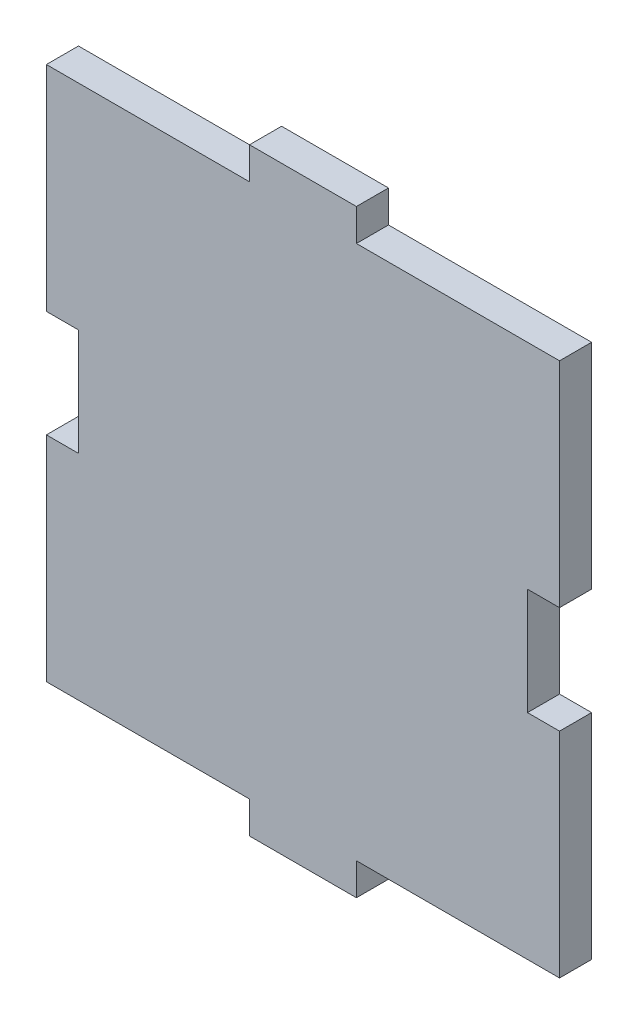
SolidWorks part; units mm, degrees
ref_plane "Front Plane" through (0, 0, 0) normal (0, 0, 1) x (1, 0, 0)
ref_plane "Top Plane" through (0, 0, 0) normal (0, 1, 0) x (1, 0, 0)
ref_plane "Right Plane" through (0, 0, 0) normal (1, 0, 0) x (0, 0, -1)
sketch "Sketch1" plane through (0, 0, 0) normal (0, 0, 1) x (1, 0, 0)
  line L0 (-5, -25) -> (-5, -28)
  line L1 (24, -25) -> (5, -25)
  line L2 (24, -25) -> (24, -5)
  line L3 (24, 25) -> (5, 25)
  line L4 (-24, -25) -> (-24, -5)
  line L5 (24, -25) -> (-24, 25) construction
  line L6 (24, 25) -> (-24, -25) construction
  line L7 (-5, -28) -> (5, -28)
  line L8 (5, -28) -> (5, -25)
  line L9 (-5, 25) -> (-5, 28)
  line L10 (-5, 28) -> (5, 28)
  line L11 (5, 28) -> (5, 25)
  line L12 (-24, -5) -> (-21, -5)
  line L13 (-21, -5) -> (-21, 5)
  line L14 (-21, 5) -> (-24, 5)
  line L15 (0, 0) -> (0, 28.5) construction
  line L16 (24, -5) -> (21, -5)
  line L17 (21, 5) -> (24, 5)
  line L18 (21, -5) -> (21, 5)
  line L19 (-24, 5) -> (-24, 25)
  line L20 (24, 5) -> (24, 25)
  line L21 (-5, 25) -> (-24, 25)
  line L22 (-5, -25) -> (-24, -25)
  point P0 (0, 0)
  dimension "D1" = 50
  dimension "D2" = 48
  dimension "D3" = 10
  dimension "D4" = 19
  dimension "D5" = 3
  dimension "D6" = 10
  dimension "D7" = 3
  dimension "D8" = 10
  dimension "D9" = 20
  dimension "D10" = 3
extrude "Boss-Extrude1" add sketch "Sketch1" along normal blind 3
